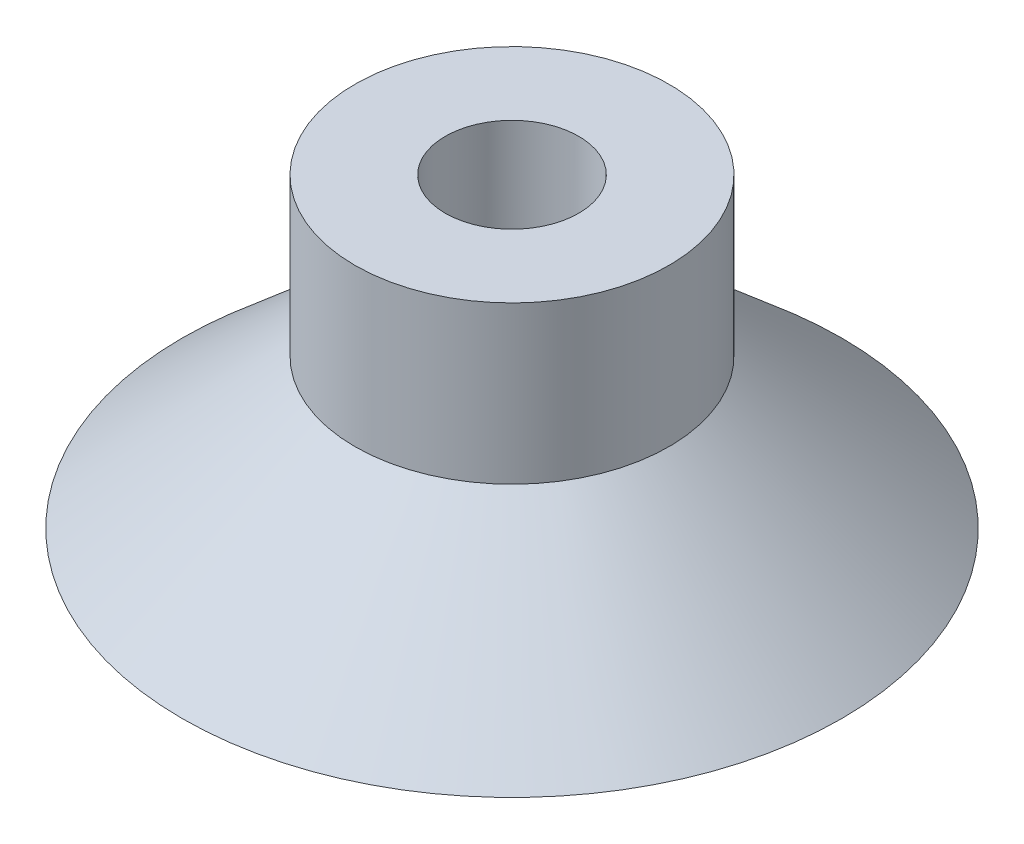
SolidWorks part; units mm, degrees
material "Silicon Rubber"
ref_plane "Front Plane" through (0, 0, 0) normal (0, 0, 1) x (1, 0, 0)
ref_plane "Top Plane" through (0, 0, 0) normal (0, 1, 0) x (1, 0, 0)
ref_plane "Right Plane" through (0, 0, 0) normal (1, 0, 0) x (0, 0, -1)
sketch "Sketch1" plane through (0, 0, 0) normal (0, 0, 1) x (1, 0, 0)
  line L0 (0, 59.4317) -> (0, -50.5959) construction
  line L1 (0, 0) -> (21, 0)
  line L2 (21, 0) -> (10, 9.5)
  line L3 (10, 9.5) -> (10, 19.5)
  line L4 (10, 19.5) -> (0, 19.5)
  line L5 (0, 19.5) -> (0, 0)
  dimension "D1" = 10
  dimension "D2" = 9.5
  dimension "D3" = 42
  dimension "D4" = 20
revolve "Revolve1" add sketch "Sketch1" angle 360 about L0
sketch "Sketch2" plane through (0, 0, 0) normal (0, 0, 1) x (1, 0, 0)
  line L0 (0, 26.1526) -> (0, -10.4433) construction
  line L1 (0, 8) -> (10.9719, 8)
  line L2 (10.9719, 8) -> (20.235, 0)
  line L3 (-21, 0) -> (21, 0) construction
  line L4 (20.235, 0) -> (0, 0)
  line L5 (0, 0) -> (0, 8)
  line L6 (10, 9.5) -> (-10, 9.5) construction
  line L7 (21, 0) -> (10, 9.5) construction
  dimension "D1" = 0.5
  dimension "D2" = 1.5
revolve "Cut-Revolve1" cut sketch "Sketch2" angle 360 about L0
hole_wizard "M10 Tapped Hole1" positions "Sketch4" profile "Sketch3" tap size "M10" standard "ISO"
sketch "Sketch4" plane through (0, 19.5, 0) normal (0, 1, 0) x (1, 0, 0)
  point P0 (0, 0)
sketch "Sketch3" plane through (0, 19.5, 0) normal (1, 0, 0) x (0, 0, 1)
  line L0 (0, 0) -> (0, 27.0537)
  line L1 (0, 27.0537) -> (4.25, 24.5)
  line L2 (4.25, 24.5) -> (4.25, 0)
  line L5 (4.25, 0) -> (0, 0)
  line L10 (0, 27.0537) -> (-4.25, 24.5) construction
  line L11 (0, -6.35) -> (0, 107.95) construction
  dimension "Tap Drill Dia." = 8.5
  dimension "Tap Drill Depth" = 24.5
  dimension "Drill Angle" = 118
cosmetic thread "Hole Thread1" parameters "D1"=11.5, "D2"=10
